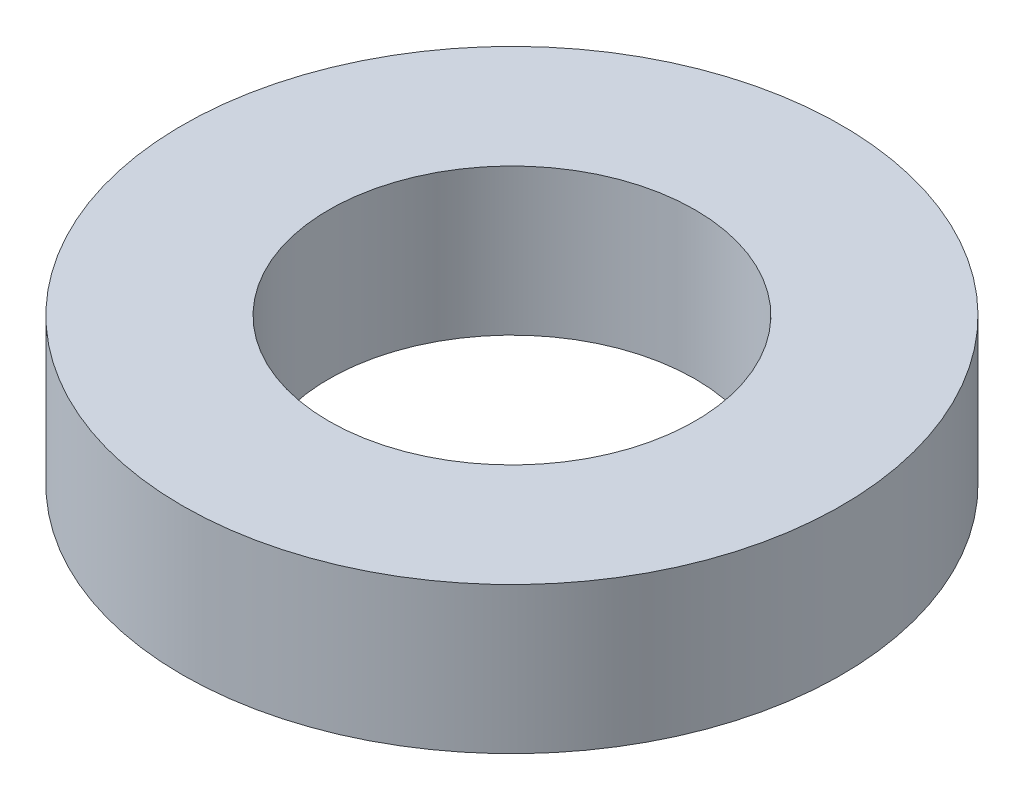
SolidWorks part; units mm, degrees
material "Aleación 1060"
ref_plane "Alzado" through (0, 0, 0) normal (0, 0, 1) x (1, 0, 0)
ref_plane "Planta" through (0, 0, 0) normal (0, 1, 0) x (1, 0, 0)
ref_plane "Vista lateral" through (0, 0, 0) normal (1, 0, 0) x (0, 0, -1)
sketch "Croquis1" plane through (0, 0, 0) normal (0, 1, 0) x (1, 0, 0)
  circle A0 centre (0, 0) radius 3.9688
  circle A1 centre (0, 0) radius 7.1438
  dimension "D1" = 7.9375
  dimension "D2" = 14.2875
extrude "Saliente-Extruir1" add sketch "Croquis1" along normal blind 3.175
